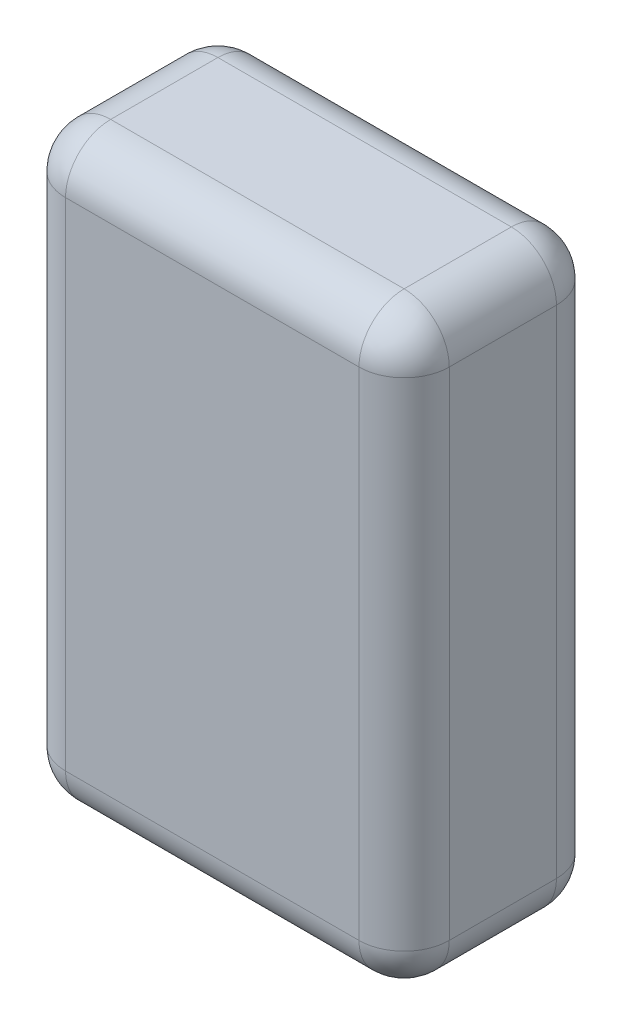
SolidWorks part; units mm, degrees
ref_plane "Front" through (0, 0, 0) normal (0, 0, 1) x (1, 0, 0)
ref_plane "Top" through (0, 0, 0) normal (0, 1, 0) x (1, 0, 0)
ref_plane "Right" through (0, 0, 0) normal (1, 0, 0) x (0, 0, -1)
sketch "草图1" plane through (0, 0, 0) normal (0, 0, 1) x (1, 0, 0)
  line L1 (-8.5, -13) -> (8.5, -13)
  line L2 (-8.5, -13) -> (-8.5, 13)
  line L3 (-8.5, 13) -> (8.5, 13)
  line L4 (8.5, -13) -> (8.5, 13)
  line L5 (-8.5, -13) -> (8.5, 13) construction
  line L6 (-8.5, 13) -> (8.5, -13) construction
  point P0 (0, 0)
  dimension "D1" = 17
  dimension "D2" = 26
extrude "凸台-拉伸1" add sketch "草图1" along normal blind 8.75
fillet "圆角1" radius 2 12 edges at (-8.5, 13, 4.375) (-8.5, -13, 4.375) (0, -13, 8.75) (-8.5, 0, 8.75) (0, 13, 8.75) (0, 13, 0) (-8.5, 0, 0) (0, -13, 0) (8.5, -13, 4.375) (8.5, 0, 8.75) (8.5, 13, 4.375) (8.5, 0, 0)
